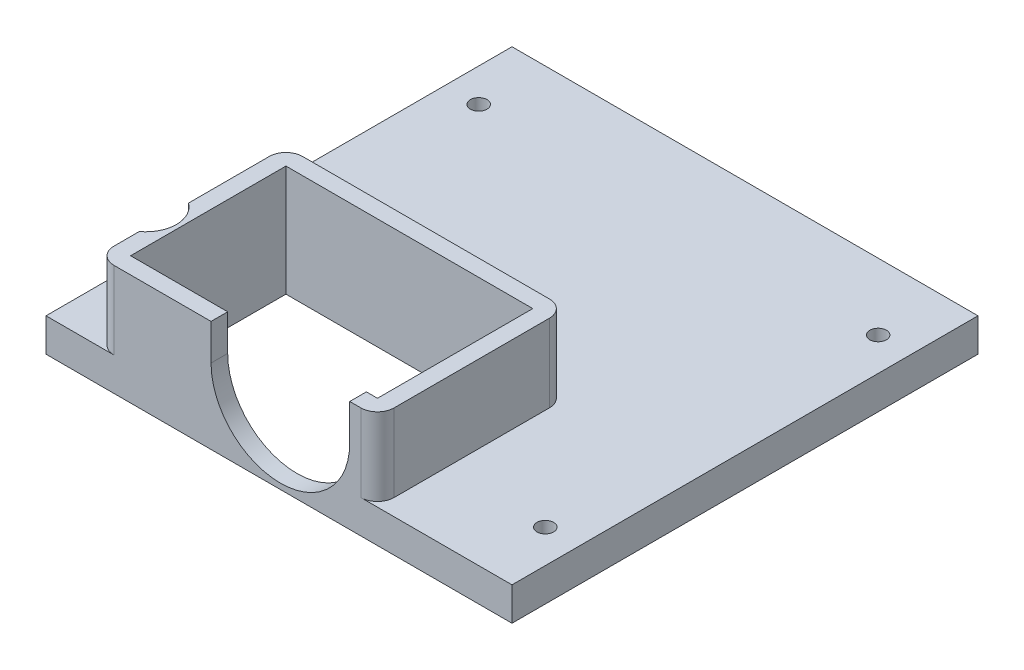
SolidWorks part; units mm, degrees
material "PVB"
ref_plane "Front Plane" through (0, 0, 0) normal (0, 0, 1) x (1, 0, 0)
ref_plane "Top Plane" through (0, 0, 0) normal (0, 1, 0) x (1, 0, 0)
ref_plane "Right Plane" through (0, 0, 0) normal (1, 0, 0) x (0, 0, -1)
sketch "Sketch1" plane through (0, 0, 0) normal (0, 1, 0) x (1, 0, 0)
  line L1 (0, 0) -> (84, 0)
  line L2 (0, 0) -> (0, 84)
  line L3 (0, 84) -> (84, 84)
  line L4 (84, 0) -> (84, 84)
  dimension "D1" = 84
  dimension "D2" = 84
extrude "Boss-Extrude1" add sketch "Sketch1" along normal blind 6
sketch "Sketch2" plane through (0, 6, 0) normal (0, 1, 0) x (1, 0, 0)
  line L0 (84, 84) -> (0, 84) construction
  line L1 (0, 84) -> (0, 0) construction
  line L2 (0, 0) -> (84, 0) construction
  line L3 (84, 0) -> (84, 84) construction
  circle A0 centre (6, 72) radius 1.5
  circle A1 centre (6, 12) radius 1.5
  circle A2 centre (78, 12) radius 1.5
  circle A3 centre (78, 72) radius 1.5
  dimension "D1" = 3
  dimension "D2" = 3
  dimension "D3" = 3
  dimension "D4" = 3
  dimension "D6" = 6
  dimension "D7" = 12
  dimension "D8" = 6
  dimension "D9" = 6
  dimension "D10" = 12
  dimension "D11" = 6
  dimension "D5" = 12
  dimension "D12" = 12
extrude "Cut-Extrude1" cut sketch "Sketch2" against normal through all
ref_plane "Plane1" through (0, 0, -42) normal (0, 0, 1) x (1, 0, 0)
sketch "Sketch4" plane through (0, 6, 0) normal (0, 1, 0) x (1, 0, 0)
  line L0 (3, 21) -> (3, 9)
  line L1 (3, 9) -> (13, 9)
  line L2 (13, 15) -> (8, 21)
  line L3 (3, 21) -> (8, 21)
  line L4 (8, 21) -> (13, 15)
  line L5 (13, 15) -> (13, 9)
  line L6 (0, 84) -> (0, 0) construction
  line L7 (0, 0) -> (84, 0) construction
  circle A0 centre (6, 12) radius 1.5
  circle A1 centre (6, 12) radius 1.5 construction
  dimension "D1" = 3
  dimension "D2" = 9
  dimension "D3" = 12
  dimension "D4" = 10
  dimension "D5" = 6
  dimension "D6" = 5
ref_plane "Plane2" through (42, 0, 0) normal (-1, 0, 0) x (0, 0, 1)
sketch "Sketch5" plane through (0, 6, 0) normal (0, 1, 0) x (1, 0, 0)
  line L0 (9.25, 34) -> (9.25, 0)
  line L1 (9.25, 34) -> (59.75, 34)
  line L2 (9.25, 0) -> (59.75, 0)
  line L3 (59.75, 34) -> (59.75, 0)
  line L4 (9.25, 34) -> (59.75, 0) construction
  line L5 (9.25, 0) -> (59.75, 34) construction
  line L6 (42, 3.3) -> (42, -3.3) construction
  line L12 (0, 0) -> (84, 0) construction
  point P1 (34.5, 17)
  dimension "D1" = 50.5
  dimension "D2" = 34
  dimension "D3" = 7.5
extrude "Boss-Extrude2" add sketch "Sketch5" along normal blind 22
sketch "Sketch6" plane through (0, 28, 0) normal (0, 1, 0) x (1, 0, 0)
  line L14 (56.75, 31) -> (12.25, 31)
  line L15 (12.25, 31) -> (12.25, 3)
  line L16 (12.25, 3) -> (56.75, 3)
  line L17 (56.75, 3) -> (56.75, 31)
  line L18 (56.75, 31) -> (12.25, 31)
  line L19 (12.25, 31) -> (12.25, 3)
  line L20 (12.25, 3) -> (56.75, 3)
  line L21 (56.75, 3) -> (56.75, 31)
  dimension "D1" = 3
extrude "Cut-Extrude5" cut sketch "Sketch6" against normal blind 25
fillet "Fillet1" radius 3 4 edges at (9.25, 17, -34) (59.75, 17, 0) (59.75, 17, -34) (9.25, 17, 0)
sketch "Sketch8" plane through (0, 0, 0) normal (0, 0, 1) x (1, 0, 0)
  line L1 (0, 0) -> (84, 0) construction
  line L3 (59.75, 28) -> (59.75, 6) construction
  circle A0 centre (42.25, 13.5) radius 12.5
  dimension "D2" = 25
  dimension "D1" = 17.5
  dimension "D3" = 13.5
extrude "Cut-Extrude6" cut sketch "Sketch8" against normal blind 10
sketch "Sketch9" plane through (0, 0, 0) normal (0, 0, 1) x (1, 0, 0)
  line L0 (0, 0) -> (84, 0) construction
  line L1 (0, 28) -> (84, 28)
  line L2 (0, 28) -> (0, 20)
  line L3 (0, 20) -> (84, 20)
  line L4 (84, 28) -> (84, 20)
  line L5 (84, 6) -> (84, 0) construction
  line L6 (0, 6) -> (0, 0) construction
  line L7 (12.25, 28) -> (56.75, 28) construction
  dimension "D1" = 20
extrude "Cut-Extrude7" cut sketch "Sketch9" against normal through all both and the other way through all
sketch "Sketch11" plane through (0, 0, 0) normal (0, -1, 0) x (1, 0, 0)
  line L0 (3, -9) -> (13, -9)
  line L1 (13, -9) -> (13, -15)
  line L2 (13, -15) -> (8, -21)
  line L3 (8, -21) -> (3, -21)
  line L4 (3, -21) -> (3, -9)
extrude "Cut-Extrude8" cut sketch "Sketch11" against normal blind 3
mirror "Mirror1" about plane through (0, 0, -42) normal (0, 0, 1) of "Cut-Extrude8" second plane through (42, 0, 0) second plane normal (-1, 0, 0)
sketch "Sketch13" plane through (0, 20, 0) normal (0, 1, 0) x (1, 0, 0)
  line L12 (52.9271, 0) -> (56.75, 0)
  line L13 (59.75, 3) -> (59.75, 31)
  line L14 (56.75, 34) -> (12.25, 34)
  line L15 (9.25, 31) -> (9.25, 3)
  line L16 (12.25, 0) -> (31.5729, 0)
  line L17 (12.25, 0) -> (31.5729, 0)
  line L18 (31.5729, 0) -> (31.5729, 3)
  line L19 (31.5729, 0) -> (31.5729, 3)
  line L20 (31.5729, 3) -> (12.25, 3)
  line L21 (31.5729, 3) -> (12.25, 3)
  line L22 (12.25, 3) -> (12.25, 31)
  line L23 (12.25, 3) -> (12.25, 31)
  line L24 (52.9271, 0) -> (56.75, 0)
  line L25 (59.75, 3) -> (59.75, 31)
  line L26 (56.75, 34) -> (12.25, 34)
  line L27 (9.25, 31) -> (9.25, 3)
  line L37 (12.25, 31) -> (56.75, 31)
  line L38 (12.25, 31) -> (56.75, 31)
  line L39 (56.75, 31) -> (56.75, 3)
  line L40 (56.75, 31) -> (56.75, 3)
  line L41 (56.75, 3) -> (52.9271, 3)
  line L42 (56.75, 3) -> (52.9271, 3)
  line L43 (52.9271, 3) -> (52.9271, 0)
  line L44 (52.9271, 3) -> (52.9271, 0)
  circle A0 centre (6, 12) radius 1.5 construction
  circle A1 centre (6, 12) radius 1.5
  circle A2 centre (6, 12) radius 5.5
  arc A11 (56.75, 0) -> (59.75, 3) centre (56.75, 3) ccw
  arc A12 (56.75, 0) -> (59.75, 3) centre (56.75, 3) ccw
  arc A13 (59.75, 31) -> (56.75, 34) centre (56.75, 31) ccw
  arc A14 (59.75, 31) -> (56.75, 34) centre (56.75, 31) ccw
  arc A15 (12.25, 34) -> (9.25, 31) centre (12.25, 31) ccw
  arc A24 (12.25, 34) -> (9.25, 31) centre (12.25, 31) ccw
  arc A25 (9.25, 3) -> (12.25, 0) centre (12.25, 3) ccw
  arc A26 (9.25, 3) -> (12.25, 0) centre (12.25, 3) ccw
  dimension "D2" = 11
  dimension "D1" = 0
extrude "Cut-Extrude9" cut sketch "Sketch13" against normal up to surface (14 mm away) contours L27 A2 L23
sketch "Sketch14" plane through (0, 0, 0) normal (0, 0, 1) x (1, 0, 0)
  line L0 (29.75, 13.5) -> (29.75, 20)
  line L1 (31.5729, 20) -> (12.25, 20) construction
  line L2 (29.75, 20) -> (31.5729, 20)
  line L3 (31.5729, 20) -> (29.75, 13.5)
  arc A0 (31.5729, 20) -> (52.9271, 20) centre (42.25, 13.5) ccw construction
extrude "Cut-Extrude10" cut sketch "Sketch14" against normal blind 10
sketch "Sketch15" plane through (0, 0, 0) normal (0, 0, 1) x (1, 0, 0)
  line L0 (54.75, 20) -> (54.75, 13.5)
  line L1 (56.75, 20) -> (52.9271, 20) construction
  line L2 (54.75, 20) -> (52.9271, 20)
  line L3 (52.9271, 20) -> (54.75, 13.5)
  arc A0 (29.75, 13.5) -> (52.9271, 20) centre (42.25, 13.5) ccw construction
extrude "Cut-Extrude11" cut sketch "Sketch15" against normal blind 10
sketch "Sketch17" plane through (0, 0, 0) normal (0, -1, 0) x (1, 0, 0)
  line L0 (8.8333, -9) -> (8.8333, -20)
  line L1 (13, -9) -> (3, -9) construction
  line L2 (8, -21) -> (13, -15) construction
  line L3 (8.8333, -20) -> (13, -15)
  line L4 (13, -15) -> (13, -9)
  line L5 (13, -9) -> (8.8333, -9)
  dimension "D1" = 11
extrude "Boss-Extrude3" add sketch "Sketch17" against normal up to surface (3 mm away) up to face at (7.7, 3, -15.18)
sketch "Sketch18" plane through (0, 3, 0) normal (0, 1, 0) x (1, 0, 0)
  line L8 (35.4677, 3) -> (35.4677, 10)
  line L9 (35.4677, 10) -> (49.0323, 10)
  line L10 (49.0323, 10) -> (49.0323, 3)
  line L11 (49.0323, 3) -> (56.75, 3)
  line L12 (56.75, 3) -> (56.75, 31)
  line L13 (56.75, 31) -> (12.25, 31)
  line L14 (12.25, 31) -> (12.25, 3)
  line L15 (12.25, 3) -> (35.4677, 3)
extrude "Cut-Extrude14" cut sketch "Sketch18" against normal blind 4
sketch "Sketch20" plane through (0, 0, 0) normal (0, -1, 0) x (1, 0, 0)
  line L1 (35.4677, -10) -> (49.0323, -10)
  line L2 (35.4677, -10) -> (35.4677, -3)
  line L3 (35.4677, -3) -> (49.0323, -3)
  line L4 (49.0323, -10) -> (49.0323, -3)
extrude "Cut-Extrude15" cut sketch "Sketch20" against normal blind 4
